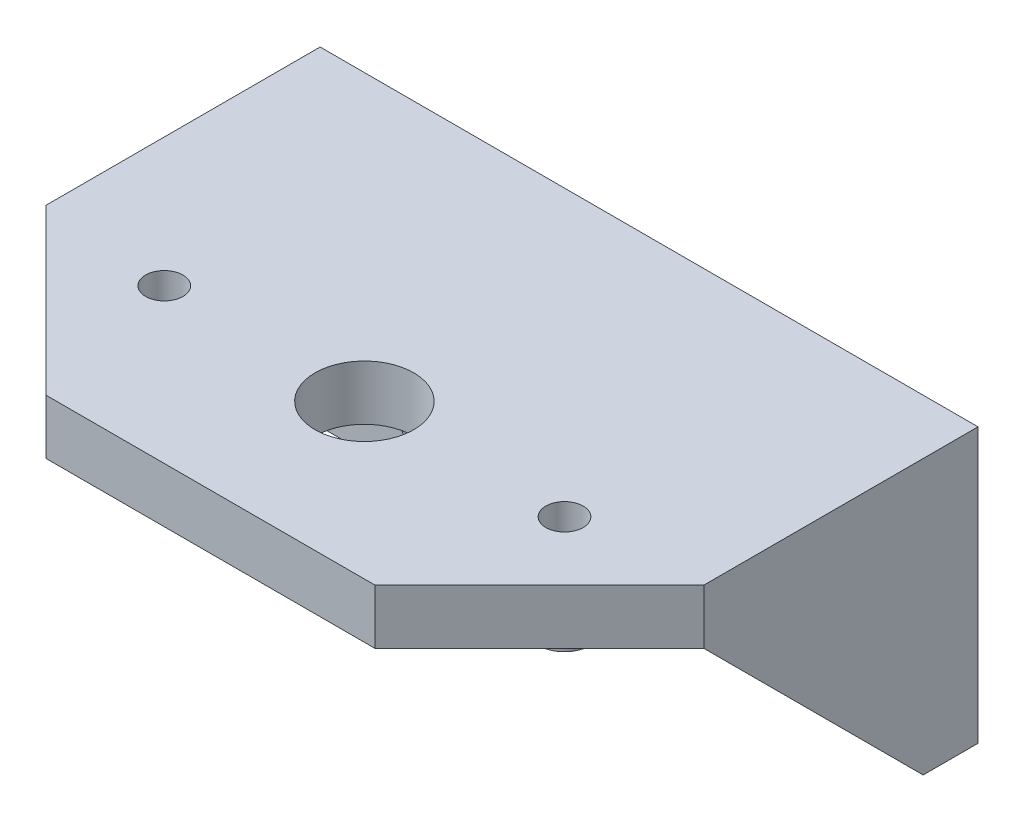
SolidWorks part; units mm, degrees
material "Custom Plastic"
ref_plane "Front Plane" through (0, 0, 0) normal (0, 0, 1) x (1, 0, 0)
ref_plane "Top Plane" through (0, 0, 0) normal (0, 1, 0) x (1, 0, 0)
ref_plane "Right Plane" through (0, 0, 0) normal (1, 0, 0) x (0, 0, -1)
sketch "Sketch1" plane through (0, 0, 0) normal (0, 0, 1) x (1, 0, 0)
  line L0 (264.0238, 235.9236) -> (-40.7762, 235.9236) construction
  line L1 (111.6238, 235.9236) -> (91.6238, 235.9236)
  line L2 (111.6238, 235.9236) -> (111.6238, 210.9236)
  line L3 (111.6238, 210.9236) -> (91.6238, 210.9236)
  line L4 (91.6238, 235.9236) -> (91.6238, 210.9236)
  line L5 (194.0505, -68.9166) -> (194.0505, -53.9166) construction
  line L6 (194.0505, -68.9166) -> (194.0505, -53.9166)
  line L8 (91.6238, 235.9236) -> (131.6238, 235.9236)
  line L9 (91.6238, 235.9236) -> (91.6238, 210.9236)
  line L10 (91.6238, 210.9236) -> (131.6238, 210.9236)
  line L11 (131.6238, 235.9236) -> (131.6238, 210.9236)
  line L12 (131.6238, 210.9236) -> (126.6238, 210.9236)
  line L13 (131.6238, 210.9236) -> (131.6238, 215.9236)
  line L14 (131.6238, 215.9236) -> (126.6238, 215.9236) construction
  line L15 (126.6238, 210.9236) -> (126.6238, 215.9236) construction
  line L16 (131.6238, 235.9236) -> (126.6238, 235.9236)
  line L17 (131.6238, 235.9236) -> (131.6238, 225.9236)
  line L18 (131.6238, 225.9236) -> (126.6238, 225.9236) construction
  line L19 (126.6238, 235.9236) -> (126.6238, 225.9236) construction
  line L20 (91.6238, 235.9236) -> (96.6238, 235.9236)
  line L21 (91.6238, 235.9236) -> (91.6238, 225.9236)
  line L22 (91.6238, 225.9236) -> (96.6238, 225.9236) construction
  line L23 (96.6238, 235.9236) -> (96.6238, 225.9236) construction
  line L24 (91.6238, 210.9236) -> (96.6238, 210.9236)
  line L25 (91.6238, 210.9236) -> (91.6238, 215.9236)
  line L26 (91.6238, 215.9236) -> (96.6238, 215.9236) construction
  line L27 (96.6238, 210.9236) -> (96.6238, 215.9236) construction
  line L28 (131.6238, 210.9236) -> (141.6238, 210.9236)
  line L29 (131.6238, 210.9236) -> (131.6238, 235.9236)
  line L30 (131.6238, 235.9236) -> (141.6238, 235.9236)
  line L31 (141.6238, 210.9236) -> (141.6238, 235.9236)
  line L32 (91.6238, 210.9236) -> (81.6238, 210.9236)
  line L33 (91.6238, 210.9236) -> (91.6238, 235.9236)
  line L34 (91.6238, 235.9236) -> (81.6238, 235.9236)
  line L35 (81.6238, 210.9236) -> (81.6238, 235.9236)
  circle A0 centre (126.6238, 225.9236) radius 1.7
  circle A1 centre (126.6238, 215.9236) radius 1.7
  circle A2 centre (96.6238, 215.9236) radius 1.7
  circle A3 centre (96.6238, 225.9236) radius 1.7
extrude "Boss-Extrude1" add sketch "Sketch1" along normal blind 5 contours L28 L31 L30 L16 L11 L12 A1 A0 | L11 L8 L2 L10 | L1 L4 L9 L3 L2 | L35 L32 L24 L4 L9 L20 L34 A3 A2
sketch "Sketch3" plane through (0, 235.9236, 0) normal (0, 1, 0) x (1, 0, 0)
  line L0 (129.8738, -25.9619) -> (131.6415, -27.7297)
  line L2 (93.3738, -25.9619) -> (90.3686, -28.9671)
  line L4 (81.6238, -5) -> (141.6238, -5) construction
  line L5 (81.6238, -5) -> (141.6238, -5)
  line L6 (81.6238, -40) -> (141.6238, -40)
  line L7 (124.9238, -5) -> (128.3238, -5) construction
  line L8 (124.9238, -5) -> (128.3238, -5)
  line L9 (128.3238, -5) -> (124.9238, -5)
  line L10 (-40.7762, -50) -> (264.0238, -50) construction
  line L11 (141.6238, -5) -> (141.6238, -40)
  line L12 (81.6238, -5) -> (81.6238, -40)
  line L13 (-40.7762, -50) -> (264.0238, -50)
  circle A0 centre (111.6238, -25.9619) radius 4.5
  circle A2 centre (129.8738, -25.9619) radius 2.5
  circle A3 centre (93.3738, -25.9619) radius 2.5
  arc A4 (102.6962, -35.7301) -> (121.0103, -35.7301) centre (111.8532, -25.8105) ccw construction
  arc A5 (102.6962, -35.7301) -> (121.0103, -35.7301) centre (111.8532, -25.8105) ccw
  point P12 (111.6238, -25.9619)
extrude "Boss-Extrude2" add sketch "Sketch3" against normal blind 5
sketch "Sketch4" plane through (0, 0, 5) normal (0, 0, 1) x (1, 0, 0)
  circle A0 centre (126.6238, 215.9236) radius 3
  circle A1 centre (126.6238, 225.9236) radius 3
  circle A2 centre (96.6238, 225.9236) radius 3
  circle A3 centre (96.6238, 215.9236) radius 3
extrude "Cut-Extrude1" cut sketch "Sketch4" against normal blind 3
sketch "Sketch6" plane through (141.6238, 0, 0) normal (1, 0, 0) x (0, 0, -1)
  line L0 (-5, 210.9236) -> (-40, 230.9236)
  line L6 (0, 210.9236) -> (0, 235.9236)
  line L7 (0, 235.9236) -> (-40, 235.9236)
  line L9 (-40, 230.9236) -> (-5, 230.9236)
  line L10 (-5, 230.9236) -> (-5, 210.9236)
  line L11 (-5, 210.9236) -> (0, 210.9236)
  line L12 (0, 210.9236) -> (0, 235.9236)
  line L13 (0, 235.9236) -> (-40, 235.9236)
  line L17 (-5, 210.9236) -> (0, 210.9236)
  line L18 (-40, 235.9236) -> (-40, 230.9236)
  line L21 (-40, 235.9236) -> (-40, 230.9236)
  dimension "D1" = 0
sketch "Sketch7" plane through (81.6238, 0, 0) normal (-1, 0, 0) x (0, 0, 1)
  line L0 (40, 230.9236) -> (5, 210.9236)
  line L6 (0, 235.9236) -> (0, 210.9236)
  line L7 (0, 210.9236) -> (5, 210.9236)
  line L8 (5, 210.9236) -> (5, 230.9236)
  line L10 (5, 230.9236) -> (40, 230.9236)
  line L11 (40, 235.9236) -> (0, 235.9236)
  line L12 (0, 235.9236) -> (0, 210.9236)
  line L13 (0, 210.9236) -> (5, 210.9236)
  line L17 (40, 235.9236) -> (0, 235.9236)
  line L18 (40, 230.9236) -> (40, 235.9236)
  line L21 (40, 230.9236) -> (40, 235.9236)
  dimension "D1" = 0
sketch "Sketch9" plane through (141.6238, 0, 0) normal (1, 0, 0) x (0, 0, -1)
  line L0 (-5, 210.9236) -> (-20, 225.9236)
  line L1 (-35, 210.9236) -> (-20, 225.9236)
  line L8 (0, 210.9236) -> (0, 235.9236)
  line L9 (0, 235.9236) -> (-40, 235.9236)
  line L10 (-40, 235.9236) -> (-40, 230.9236)
  line L11 (-40, 235.9236) -> (-40, 230.9236)
  line L14 (-5, 230.9236) -> (-5, 210.9236)
  line L15 (-5, 210.9236) -> (0, 210.9236)
  line L16 (0, 210.9236) -> (0, 235.9236)
  line L17 (0, 235.9236) -> (-40, 235.9236)
  line L22 (-5, 230.9236) -> (-5, 210.9236)
  line L23 (-5, 210.9236) -> (0, 210.9236)
  line L26 (-40, 230.9236) -> (-5, 230.9236)
  line L27 (-40, 230.9236) -> (-5, 230.9236)
  dimension "D1" = 0
sketch "Sketch10" plane through (81.6238, 0, 0) normal (-1, 0, 0) x (0, 0, 1)
  line L0 (35, 210.9236) -> (20, 225.9236)
  line L1 (5, 210.9236) -> (20, 225.9236)
  line L8 (0, 235.9236) -> (0, 210.9236)
  line L9 (0, 210.9236) -> (5, 210.9236)
  line L10 (5, 210.9236) -> (5, 230.9236)
  line L11 (40, 230.9236) -> (40, 235.9236)
  line L12 (40, 230.9236) -> (40, 235.9236)
  line L13 (5, 230.9236) -> (40, 230.9236)
  line L15 (40, 235.9236) -> (0, 235.9236)
  line L16 (0, 235.9236) -> (0, 210.9236)
  line L17 (0, 210.9236) -> (5, 210.9236)
  line L23 (40, 235.9236) -> (0, 235.9236)
  dimension "D1" = 0
sketch "Sketch11" plane through (0, 230.9236, 0) normal (0, -1, 0) x (1, 0, 0)
  circle A4 centre (93.3738, 25.9619) radius 1.7
  circle A5 centre (129.8738, 25.9619) radius 1.7
  circle A6 centre (129.8738, 25.9619) radius 2.35
  circle A7 centre (93.3738, 25.9619) radius 2.35
extrude "Boss-Extrude3" add sketch "Sketch11" along normal blind 4 separate body
sketch "Sketch12" plane through (0, 230.9236, 0) normal (0, 1, 0) x (1, 0, 0)
  circle A0 centre (129.8738, -25.9619) radius 2.6586
  circle A1 centre (129.8738, -25.9619) radius 1.7
  circle A2 centre (93.3738, -25.9619) radius 1.7 construction
  circle A3 centre (93.3738, -25.9619) radius 1.7
  circle A4 centre (93.3738, -25.9619) radius 2.827
extrude "Boss-Extrude4" add sketch "Sketch12" along normal up to surface (5 mm away) up to face at (111.6238, 235.9236, 20)
chamfer "Chamfer1" distance 15 2 edges at (141.6238, 233.4236, 40) (81.6238, 233.4236, 40)
sketch "Sketch13" plane through (81.6238, 0, 0) normal (-1, 0, 0) x (0, 0, 1)
  line L0 (25, 230.9236) -> (5, 210.9236)
  line L6 (5, 230.9236) -> (25, 230.9236)
  line L7 (25, 230.9236) -> (25, 235.9236)
  line L8 (25, 235.9236) -> (0, 235.9236)
  line L9 (0, 235.9236) -> (0, 210.9236)
  line L10 (0, 210.9236) -> (5, 210.9236)
  line L11 (5, 210.9236) -> (5, 230.9236)
  line L12 (5, 230.9236) -> (25, 230.9236)
  line L13 (25, 230.9236) -> (25, 235.9236)
  line L14 (25, 235.9236) -> (0, 235.9236)
  line L15 (0, 235.9236) -> (0, 210.9236)
  line L16 (0, 210.9236) -> (5, 210.9236)
  line L17 (5, 210.9236) -> (5, 230.9236)
  line M7 (5, 230.9236) -> (25, 230.9236)
  line M8 (25, 230.9236) -> (25, 235.9236)
  line M9 (25, 235.9236) -> (0, 235.9236)
  line M10 (0, 235.9236) -> (0, 210.9236)
  line M11 (0, 210.9236) -> (5, 210.9236)
  line M12 (5, 210.9236) -> (5, 230.9236)
  dimension "D1" = 0
extrude "Boss-Extrude5" add sketch "Sketch13" against normal blind 3 contours L0 M7 M12 | M12 M7 M8 M9 M10 M11
sketch "Sketch14" plane through (141.6238, 0, 0) normal (1, 0, 0) x (0, 0, -1)
  line L0 (-5, 210.9236) -> (-25, 230.9236)
  line L6 (0, 235.9236) -> (-25, 235.9236)
  line L7 (-25, 235.9236) -> (-25, 230.9236)
  line L8 (-25, 230.9236) -> (-5, 230.9236)
  line L9 (-5, 230.9236) -> (-5, 210.9236)
  line L10 (-5, 210.9236) -> (0, 210.9236)
  line L11 (0, 210.9236) -> (0, 235.9236)
  line L12 (0, 235.9236) -> (-25, 235.9236)
  line L13 (-25, 235.9236) -> (-25, 230.9236)
  line L14 (-25, 230.9236) -> (-5, 230.9236)
  line L15 (-5, 230.9236) -> (-5, 210.9236)
  line L16 (-5, 210.9236) -> (0, 210.9236)
  line L17 (0, 210.9236) -> (0, 235.9236)
  line M7 (0, 235.9236) -> (-25, 235.9236)
  line M8 (-25, 235.9236) -> (-25, 230.9236)
  line M9 (-25, 230.9236) -> (-5, 230.9236)
  line M10 (-5, 230.9236) -> (-5, 210.9236)
  line M11 (-5, 210.9236) -> (0, 210.9236)
  line M12 (0, 210.9236) -> (0, 235.9236)
  dimension "D1" = 0
extrude "Boss-Extrude6" add sketch "Sketch14" against normal blind 3 contours L0 M10 M9 | M12 M7 M8 M9 M10 M11
chamfer "Chamfer2" distance 2 distance2 1 2 edges at (91.0238, 230.9236, 25.9619) (127.5238, 230.9236, 25.9619)
